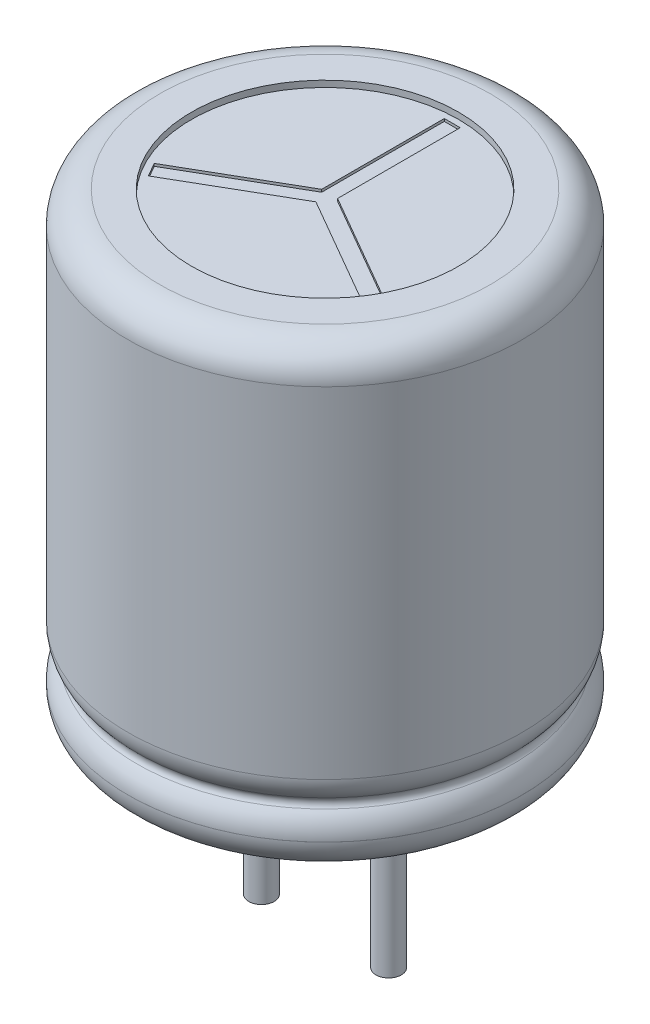
SolidWorks part; units mm, degrees
ref_plane "Front" through (0, 0, 0) normal (0, 0, 1) x (1, 0, 0)
ref_plane "Top" through (0, 0, 0) normal (0, 1, 0) x (1, 0, 0)
ref_plane "Right" through (0, 0, 0) normal (1, 0, 0) x (0, 0, -1)
sketch "Sketch1" plane through (0, 0, 0) normal (0, 0, 1) x (1, 0, 0)
  line L0 (-3, 0.4) -> (-3, 6.6)
  line L1 (0, 7) -> (-2.6, 7)
  line L2 (-2.6, 0) -> (0, 0)
  line L3 (0, 0) -> (0, 7)
  arc A0 (-2.6, 7) -> (-3, 6.6) centre (-2.6, 6.6) ccw
  arc A1 (-2.6, 0) -> (-3, 0.4) centre (-2.6, 0.4) cw
  point P6 (-3, 7)
  point P9 (-3, 0)
  dimension "D3" = 0.4
  dimension "D1" = 7
  dimension "D2" = 3
revolve "Revolve1" add sketch "Sketch1" angle 360 about L3
sketch "Sketch2" plane through (0, 0, 0) normal (0, 0, 1) x (1, 0, 0)
  line L0 (-3.1, 0.4) -> (-3.1, 0.4008)
  line L1 (-2.8825, 0.6831) -> (-3, 1.2517)
  line L3 (-3, 6.6) -> (-3, 0.4) construction
  line L7 (-2.6, 7.1) -> (-2.1, 7.1)
  line L8 (-3.1, 6.6) -> (-3.1, 0.4)
  line L9 (-3.1, 6.6) -> (-3.1, 1.2517)
  line L10 (-2.1, 7.1) -> (-2.1, 7)
  line L11 (0, 7) -> (-2.6, 7) construction
  line L12 (-2.6, -0.1) -> (-2.6, 0)
  line L13 (-2.1, 7) -> (-2.6, 7)
  line L14 (-3, 6.6) -> (-3, 1.2517)
  arc A0 (-2.6, 0) -> (-2.8825, 0.6831) centre (-2.6, 0.4) cw
  arc A1 (-2.9572, 0.9018) -> (-2.9572, 0.7507) centre (-3.0343, 0.8262) cw
  arc A2 (-2.9572, 0.9018) -> (-3.1, 1.2517) centre (-2.6, 1.2517) cw
  arc A3 (-2.9572, 0.7507) -> (-3.1, 0.4008) centre (-2.6, 0.4008) ccw
  arc A7 (-3, 6.6) -> (-2.6, 7) centre (-2.6, 6.6) cw
  arc A9 (-3.1, 0.4) -> (-2.6, -0.1) centre (-2.6, 0.4) ccw
  arc A10 (-2.6, 7.1) -> (-3.1, 6.6) centre (-2.6, 6.6) ccw
  arc A11 (-3.1, 0.4) -> (-2.6, -0.1) centre (-2.6, 0.4) ccw
  arc A12 (-2.6, 7.1) -> (-3.1, 6.6) centre (-2.6, 6.6) ccw
  point P28 (-3.1, 0.9118)
  point P31 (-3.1, 0.7407)
  dimension "D5" = 0.5
  dimension "D6" = 0.5
  dimension "D2" = 0.5
  dimension "D1" = 0.1
revolve "Revolve3" add sketch "Sketch2" angle 360 about L3
sketch "Sketch4" plane through (0, 0, 0) normal (0, 0, 1) x (1, 0, 0)
  line L1 (0, 0) -> (0, 50000) construction
  circle A0 centre (-3.4, 0.9066) radius 0.5
  dimension "D1" = 1
  dimension "D2" = 3.4
revolve "Cut-Revolve1" cut sketch "Sketch4" angle 360 about L1
sketch "Sketch3" plane through (0, 0, 0) normal (0, -1, 0) x (1, 0, 0)
  line L0 (0, 0) -> (0, 0.2232) construction
  circle A0 centre (-1, 0) radius 0.2
  circle A1 centre (1, 0) radius 0.2
  dimension "D1" = 1
  dimension "D2" = 0.4
extrude "Boss-Extrude1" add sketch "Sketch3" along normal blind 3 separate body
sketch "Sketch5" plane through (0, 7, 0) normal (0, 1, 0) x (1, 0, 0)
  line L3 (-1.7946, -0.8917) -> (-1.6696, -1.1083)
  line L4 (-1.6696, -1.1083) -> (0, -0.1443)
  line L5 (0, -0.1443) -> (1.6696, -1.1083)
  line L6 (1.6696, -1.1083) -> (1.7946, -0.8917)
  line L7 (1.7946, -0.8917) -> (0.125, 0.0722)
  line L8 (0.125, 0.0722) -> (0.125, 2)
  line L9 (0.125, 2) -> (-0.125, 2)
  line L10 (-0.125, 2) -> (-0.125, 0.0722)
  line L11 (-0.125, 0.0722) -> (-1.7946, -0.8917)
  dimension "D1" = 2
  dimension "D2" = 2
  dimension "D3" = 2
  dimension "D4" = 120
  dimension "D6" = 0.25
  dimension "D7" = 0.25
  dimension "D8" = 0.25
extrude "Cut-Extrude2" cut sketch "Sketch5" against normal blind 0.04
